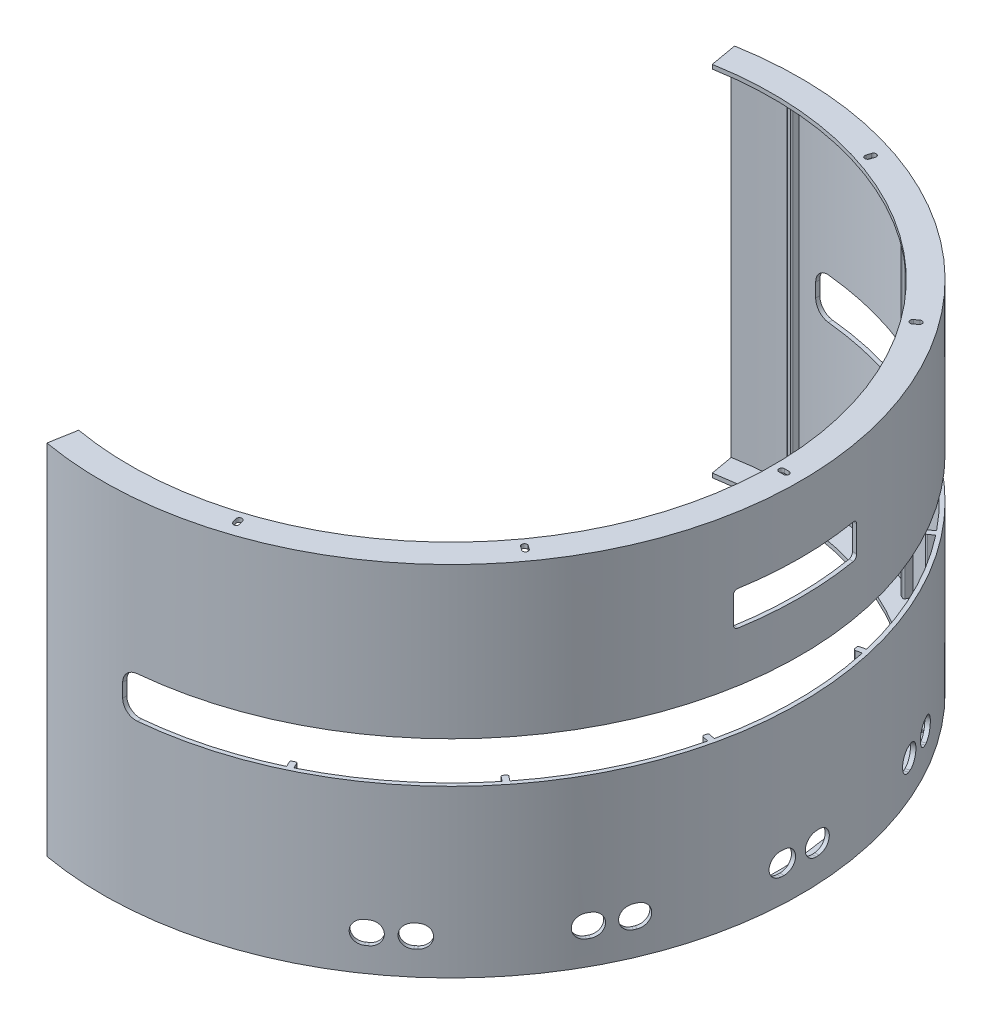
SolidWorks part; units mm, degrees
ref_plane "Front Plane" through (0, 0, 0) normal (0, 0, 1) x (1, 0, 0)
ref_plane "Top Plane" through (0, 0, 0) normal (0, 1, 0) x (1, 0, 0)
ref_plane "Right Plane" through (0, 0, 0) normal (1, 0, 0) x (0, 0, -1)
sketch "Sketch3" plane through (0, 0, 0) normal (0, 1, 0) x (1, 0, 0)
  line L0 (0, -251.5) -> (0, 251.5)
  line L1 (-44.1935, 250.6336) -> (-43.6725, 247.6791)
  line L2 (-43.6725, -247.6791) -> (-44.1935, -250.6336)
  arc A0 (0, 251.5) -> (0, -251.5) centre (0, 0) cw
  arc A1 (0, 251.5) -> (-43.6725, 247.6791) centre (0, 0) ccw
  arc A2 (0, -251.5) -> (-43.6725, -247.6791) centre (0, 0) cw
  arc A3 (0, 254.5) -> (0, -254.5) centre (0, 0) cw
  arc A4 (0, 254.5) -> (-44.1935, 250.6336) centre (0, 0) ccw
  arc A5 (0, -254.5) -> (-44.1935, -250.6336) centre (0, 0) cw
  point P4 (0, 0)
  dimension "D1" = 503
  dimension "D2" = 3
  dimension "D3" = 3
  dimension "D4" = 3
extrude "Boss-Extrude1" add sketch "Sketch3" along normal blind 255 contours A5 A3 A4 L1 A1 A0 A2 L2
sketch "Sketch6" plane through (0, 255, 0) normal (0, 1, 0) x (1, 0, 0)
  line L0 (0, -256) -> (0, 256)
  line L1 (-2, 253.0819) -> (-2, 247.0819)
  line L2 (-1, 246.0819) -> (1, 246.0819)
  line L3 (2, 247.0819) -> (2, 253.0819)
  line L4 (-2, 253.0819) -> (2, 253.0819)
  line L54 (108.0062, 228.8867) -> (105.4029, 223.4809)
  line L55 (105.87, 222.146) -> (107.6719, 221.2783)
  line L56 (109.0068, 221.7454) -> (111.6101, 227.1512)
  line L57 (108.0062, 228.8867) -> (111.6101, 227.1512)
  line L58 (196.6204, 159.3577) -> (191.9294, 155.6167)
  line L59 (191.7711, 154.2114) -> (193.0181, 152.6477)
  line L60 (194.4234, 152.4894) -> (199.1144, 156.2303)
  line L61 (196.6204, 159.3577) -> (199.1144, 156.2303)
  line L62 (246.2916, 58.2659) -> (240.442, 56.9308)
  line L63 (239.6896, 55.7333) -> (240.1347, 53.7835)
  line L64 (241.3321, 53.031) -> (247.1817, 54.3662)
  line L65 (246.2916, 58.2659) -> (247.1817, 54.3662)
  line L66 (247.1817, -54.3662) -> (241.3321, -53.031)
  line L67 (240.1347, -53.7835) -> (239.6896, -55.7333)
  line L68 (240.442, -56.9308) -> (246.2916, -58.2659)
  line L69 (247.1817, -54.3662) -> (246.2916, -58.2659)
  line L70 (199.1144, -156.2303) -> (194.4234, -152.4894)
  line L71 (193.0181, -152.6477) -> (191.7711, -154.2114)
  line L72 (191.9294, -155.6167) -> (196.6204, -159.3577)
  line L73 (199.1144, -156.2303) -> (196.6204, -159.3577)
  line L74 (111.6101, -227.1512) -> (109.0068, -221.7454)
  line L75 (107.6719, -221.2783) -> (105.87, -222.146)
  line L76 (105.4029, -223.4809) -> (108.0062, -228.8867)
  line L77 (111.6101, -227.1512) -> (108.0062, -228.8867)
  line L78 (2, -253.0819) -> (2, -247.0819)
  line L79 (1, -246.0819) -> (-1, -246.0819)
  line L80 (-2, -247.0819) -> (-2, -253.0819)
  line L81 (2, -253.0819) -> (-2, -253.0819)
  arc A2 (2, 247.0819) -> (1, 246.0819) centre (1, 247.0819) cw
  arc A3 (-2, 247.0819) -> (-1, 246.0819) centre (-1, 247.0819) ccw
  arc A26 (109.0068, 221.7454) -> (107.6719, 221.2783) centre (108.1058, 222.1792) cw
  arc A27 (105.4029, 223.4809) -> (105.87, 222.146) centre (106.3039, 223.047) ccw
  arc A28 (194.4234, 152.4894) -> (193.0181, 152.6477) centre (193.7999, 153.2712) cw
  arc A29 (191.9294, 155.6167) -> (191.7711, 154.2114) centre (192.5529, 154.8349) ccw
  arc A30 (241.3321, 53.031) -> (240.1347, 53.7835) centre (241.1096, 54.006) cw
  arc A31 (240.442, 56.9308) -> (239.6896, 55.7333) centre (240.6645, 55.9558) ccw
  arc A32 (240.442, -56.9308) -> (239.6896, -55.7333) centre (240.6645, -55.9558) cw
  arc A33 (241.3321, -53.031) -> (240.1347, -53.7835) centre (241.1096, -54.006) ccw
  arc A34 (191.9294, -155.6167) -> (191.7711, -154.2114) centre (192.5529, -154.8349) cw
  arc A35 (194.4234, -152.4894) -> (193.0181, -152.6477) centre (193.7999, -153.2712) ccw
  arc A36 (105.4029, -223.4809) -> (105.87, -222.146) centre (106.3039, -223.047) cw
  arc A37 (109.0068, -221.7454) -> (107.6719, -221.2783) centre (108.1058, -222.1792) ccw
  arc A38 (-2, -247.0819) -> (-1, -246.0819) centre (-1, -247.0819) cw
  arc A39 (2, -247.0819) -> (1, -246.0819) centre (1, -247.0819) ccw
  point P9 (0, 0)
  point P19 (2, 246.0819)
  point P22 (-2, 246.0819)
  point P23 (0, 246.0819)
  point P59 (0, 0)
  point P68 (0, 0)
  point P76 (0, 0)
  dimension "D3" = 1
  dimension "D1" = 7
  dimension "D2" = 4
  dimension "D4" = 0
  dimension "D5" = 7
  dimension "D6" = 256
  dimension "D7" = 8
extrude "Boss-Extrude2" add sketch "Sketch6" against normal blind 255 separate body
combine bodies "Combine2" operation type add bodies to combine 109 101 115 116 117 118 119 120 121
sketch "Sketch4" plane through (0, 0, 0) normal (0, 0, 1) x (1, 0, 0)
  line L0 (254.5, 0) -> (254.5, 255) construction
  line L1 (494.5, 118) -> (14.5, 118)
  line L2 (494.5, 118) -> (494.5, 148)
  line L3 (494.5, 148) -> (14.5, 148)
  line L4 (14.5, 118) -> (14.5, 148)
  line L5 (494.5, 118) -> (14.5, 148) construction
  line L6 (494.5, 148) -> (14.5, 118) construction
  line L7 (-44.1935, 0) -> (254.5, 0) construction
  point P0 (254.5, 133)
  dimension "D1" = 30
  dimension "D2" = 118
  dimension "D3" = 480
extrude "Cut-Extrude2" cut sketch "Sketch4" against normal mid plane 953
fillet "Fillet2" radius 10 4 edges at (14.5, 148, 252.5841) (14.5, 148, -252.5841) (14.5, 118, -252.5841) (14.5, 118, 252.5841)
sketch "Sketch7" plane through (0, 255, 0) normal (0, 1, 0) x (1, 0, 0)
  line L0 (-44.1935, 250.6336) -> (-40.7205, 230.9374)
  line L1 (-44.1935, -250.6336) -> (-40.7205, -230.9374)
  arc A0 (-40.7205, 230.9374) -> (-40.7205, -230.9374) centre (0, 0) cw
  arc A2 (-44.1935, 250.6336) -> (-44.1935, -250.6336) centre (0, 0) cw
  arc A3 (-44.1935, -250.6336) -> (-44.1935, 250.6336) centre (0, 0) ccw construction
extrude "Boss-Extrude3" add sketch "Sketch7" along normal blind 3 contours A2 L0 A0 L1
sketch "Sketch8" plane through (0, 255, 0) normal (0, -1, 0) x (1, 0, 0)
  line L0 (240.8, 0) -> (244.2, 0) construction
  line L1 (240.8, 2) -> (244.2, 2)
  line L2 (240.8, -2) -> (244.2, -2)
  line L3 (194.8113, -141.5387) -> (197.562, -143.5372) construction
  line L12 (195.9869, -139.9207) -> (198.7375, -141.9191)
  line L21 (193.6357, -143.1567) -> (196.3864, -145.1552)
  line L24 (74.4113, -229.0144) -> (75.462, -232.248) construction
  line L27 (76.3134, -228.3964) -> (77.3641, -231.63)
  line L28 (72.5092, -229.6324) -> (73.5598, -232.866)
  line L29 (-74.4113, -229.0144) -> (-75.462, -232.248) construction
  line L30 (-72.5092, -229.6324) -> (-73.5598, -232.866)
  line L31 (-76.3134, -228.3964) -> (-77.3641, -231.63)
  line L32 (-194.8113, -141.5387) -> (-197.562, -143.5372) construction
  line L33 (-193.6357, -143.1567) -> (-196.3864, -145.1552)
  line L34 (-195.9869, -139.9207) -> (-198.7375, -141.9191)
  line L35 (-240.8, 0) -> (-244.2, 0) construction
  line L36 (-240.8, -2) -> (-244.2, -2)
  line L37 (-240.8, 2) -> (-244.2, 2)
  line L38 (-194.8113, 141.5387) -> (-197.562, 143.5372) construction
  line L39 (-195.9869, 139.9207) -> (-198.7375, 141.9191)
  line L40 (-193.6357, 143.1567) -> (-196.3864, 145.1552)
  line L41 (-74.4113, 229.0144) -> (-75.462, 232.248) construction
  line L42 (-76.3134, 228.3964) -> (-77.3641, 231.63)
  line L43 (-72.5092, 229.6324) -> (-73.5598, 232.866)
  line L44 (74.4113, 229.0144) -> (75.462, 232.248) construction
  line L45 (72.5092, 229.6324) -> (73.5598, 232.866)
  line L46 (76.3134, 228.3964) -> (77.3641, 231.63)
  line L47 (194.8113, 141.5387) -> (197.562, 143.5372) construction
  line L48 (193.6357, 143.1567) -> (196.3864, 145.1552)
  line L49 (195.9869, 139.9207) -> (198.7375, 141.9191)
  circle A1 centre (242.5, 0) radius 1.7 construction
  arc A2 (240.8, 2) -> (240.8, -2) centre (240.8, 0) ccw
  arc A3 (244.2, -2) -> (244.2, 2) centre (244.2, 0) ccw
  arc A24 (195.9869, -139.9207) -> (193.6357, -143.1567) centre (194.8113, -141.5387) ccw
  arc A25 (196.3864, -145.1552) -> (198.7375, -141.9191) centre (197.562, -143.5372) ccw
  arc A26 (76.3134, -228.3964) -> (72.5092, -229.6324) centre (74.4113, -229.0144) ccw
  arc A27 (73.5598, -232.866) -> (77.3641, -231.63) centre (75.462, -232.248) ccw
  arc A28 (-72.5092, -229.6324) -> (-76.3134, -228.3964) centre (-74.4113, -229.0144) ccw
  arc A29 (-77.3641, -231.63) -> (-73.5598, -232.866) centre (-75.462, -232.248) ccw
  arc A30 (-193.6357, -143.1567) -> (-195.9869, -139.9207) centre (-194.8113, -141.5387) ccw
  arc A31 (-198.7375, -141.9191) -> (-196.3864, -145.1552) centre (-197.562, -143.5372) ccw
  arc A32 (-240.8, -2) -> (-240.8, 2) centre (-240.8, 0) ccw
  arc A33 (-244.2, 2) -> (-244.2, -2) centre (-244.2, 0) ccw
  arc A34 (-195.9869, 139.9207) -> (-193.6357, 143.1567) centre (-194.8113, 141.5387) ccw
  arc A35 (-196.3864, 145.1552) -> (-198.7375, 141.9191) centre (-197.562, 143.5372) ccw
  arc A36 (-76.3134, 228.3964) -> (-72.5092, 229.6324) centre (-74.4113, 229.0144) ccw
  arc A37 (-73.5598, 232.866) -> (-77.3641, 231.63) centre (-75.462, 232.248) ccw
  arc A38 (72.5092, 229.6324) -> (76.3134, 228.3964) centre (74.4113, 229.0144) ccw
  arc A39 (77.3641, 231.63) -> (73.5598, 232.866) centre (75.462, 232.248) ccw
  arc A40 (193.6357, 143.1567) -> (195.9869, 139.9207) centre (194.8113, 141.5387) ccw
  arc A41 (198.7375, 141.9191) -> (196.3864, 145.1552) centre (197.562, 143.5372) ccw
  point P6 (242.5, 0)
  point P16 (196.1866, -142.5379)
  point P23 (74.9366, -230.6312)
  point P28 (0, 0)
  point P31 (-74.9366, -230.6312)
  point P35 (0, 0)
  point P39 (-196.1866, -142.5379)
  point P44 (0, 0)
  point P47 (-242.5, 0)
  point P54 (-196.1866, 142.5379)
  point P57 (0, 0)
  point P62 (-74.9366, 230.6312)
  point P69 (74.9366, 230.6312)
  point P76 (196.1866, 142.5379)
  point P81 (0, 0)
  dimension "D1" = 2
extrude "Cut-Extrude3" cut sketch "Sketch8" against normal blind 5
pattern_linear "LPattern1" count 2 spacing 258 along (0, -1, 0) of "Boss-Extrude3"
pattern_linear "LPattern2" count 2 spacing 258 along (0, -1, 0) of "Cut-Extrude3"
sketch "Sketch9" plane through (0, 0, 0) normal (0, 0, 1) x (1, 0, 0)
  line L0 (254.5, 148) -> (254.5, 258) construction
  line L1 (268.0504, 184.5) -> (240.9496, 184.5)
  line L2 (268.0504, 184.5) -> (268.0504, 209.5)
  line L3 (268.0504, 209.5) -> (240.9496, 209.5)
  line L4 (240.9496, 184.5) -> (240.9496, 209.5)
  line L5 (268.0504, 184.5) -> (240.9496, 209.5) construction
  line L6 (268.0504, 209.5) -> (240.9496, 184.5) construction
  point P0 (254.5, 197)
  dimension "D1" = 25
  dimension "D2" = 200
extrude "Cut-Extrude4" cut sketch "Sketch9" against normal mid plane 90
fillet "Fillet3" radius 3 4 edges at (248.9657, 209.5, 45) (248.9657, 184.5, 45) (248.9657, 184.5, -45) (248.9657, 209.5, -45)
sketch "Sketch10" plane through (0, 0, 0) normal (1, 0, 0) x (0, 0, -1)
  line L0 (13.75, 23) -> (11.75, 23) construction
  line L1 (13.75, 14.8) -> (11.75, 14.8)
  line L2 (13.75, 31.2) -> (11.75, 31.2)
  line L3 (0, 143.55) -> (0, -143.55) construction
  line L4 (-13.75, 23) -> (-11.75, 23) construction
  line L5 (-13.75, 14.8) -> (-11.75, 14.8)
  line L6 (-13.75, 31.2) -> (-11.75, 31.2)
  arc A0 (13.75, 14.8) -> (13.75, 31.2) centre (13.75, 23) ccw
  arc A1 (11.75, 31.2) -> (11.75, 14.8) centre (11.75, 23) ccw
  arc A2 (-13.75, 14.8) -> (-13.75, 31.2) centre (-13.75, 23) cw
  arc A3 (-11.75, 31.2) -> (-11.75, 14.8) centre (-11.75, 23) cw
  point P2 (12.75, 23)
  point P12 (-12.75, 23)
  dimension "D1" = 8.2
  dimension "D2" = 2
  dimension "D3" = 12.75
  dimension "D4" = 23
extrude "Cut-Extrude5" cut sketch "Sketch10" along normal blind 600
pattern_circular "CirPattern1" count 3 every 26 about axis through (0, 255, 0) along (0, -1, 0) of "Cut-Extrude5"
pattern_circular "CirPattern2" count 3 every 26 about axis through (0, 255, 0) along (0, -1, 0) of "Cut-Extrude5"
